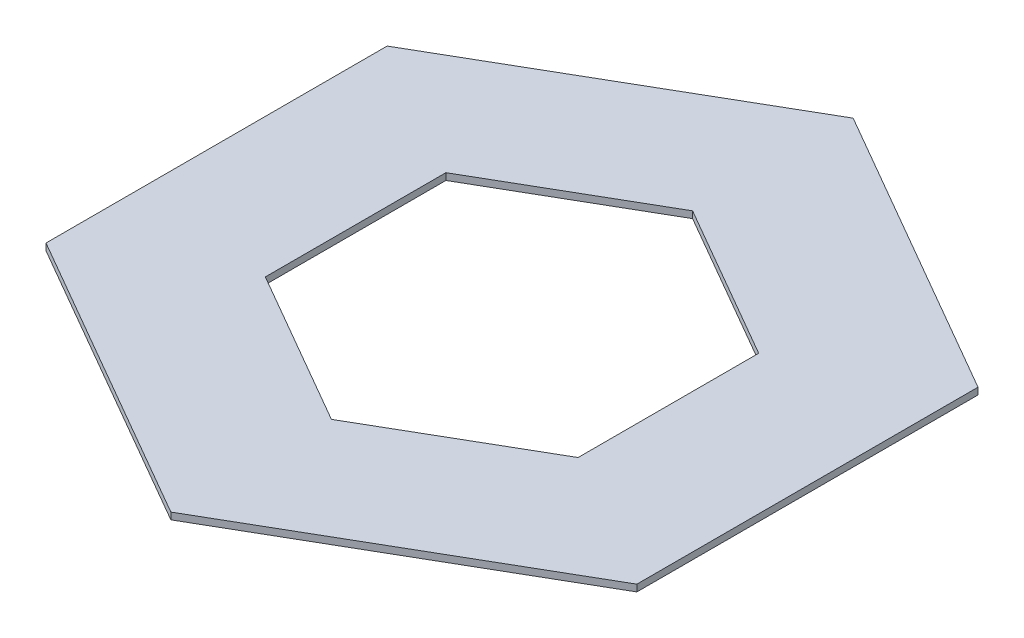
SolidWorks part; units mm, degrees
ref_plane "Plano frontal" through (0, 0, 0) normal (0, 0, 1) x (1, 0, 0)
ref_plane "Plano superior" through (0, 0, 0) normal (0, 1, 0) x (1, 0, 0)
ref_plane "Plano direito" through (0, 0, 0) normal (1, 0, 0) x (0, 0, -1)
sketch "Esboço1" plane through (0, 0, 0) normal (0, 1, 0) x (1, 0, 0)
  line L5 (-43.62, 11.0681) -> (-43.62, 25.184)
  line L6 (-43.62, 11.0681) -> (-43.62, -25.184)
  line L17 (31.3952, 32.242) -> (43.62, 25.184)
  line L18 (31.3952, 32.242) -> (0, 50.368)
  line L29 (-31.3952, -32.242) -> (-43.62, -25.184)
  line L30 (-31.3952, -32.242) -> (0, -50.368)
  line L41 (-12.2248, 43.3101) -> (0, 50.368)
  line L42 (-12.2248, 43.3101) -> (-43.62, 25.184)
  line L53 (12.2248, -43.3101) -> (0, -50.368)
  line L54 (12.2248, -43.3101) -> (43.62, -25.184)
  line L65 (43.62, -11.0681) -> (43.62, -25.184)
  line L66 (43.62, -11.0681) -> (43.62, 25.184)
extrude "Ressalto-extrusão1" add sketch "Esboço1" along normal blind 1
sketch "Esboço2" plane through (0, 0, 0) normal (0, -1, 0) x (1, 0, 0)
  line L2 (23.0917, 13.332) -> (0, 26.6639)
  line L3 (0, 26.6639) -> (-23.0917, 13.332)
  line L4 (-23.0917, 13.332) -> (-23.0917, -13.332)
  line L5 (-23.0917, -13.332) -> (0, -26.6639)
  line L6 (0, -26.6639) -> (23.0917, -13.332)
  line L7 (23.0917, -13.332) -> (23.0917, 13.332)
  circle A0 centre (0, 0) radius 23.0917 construction
extrude "Corte-extrusão1" cut sketch "Esboço2" against normal through all
